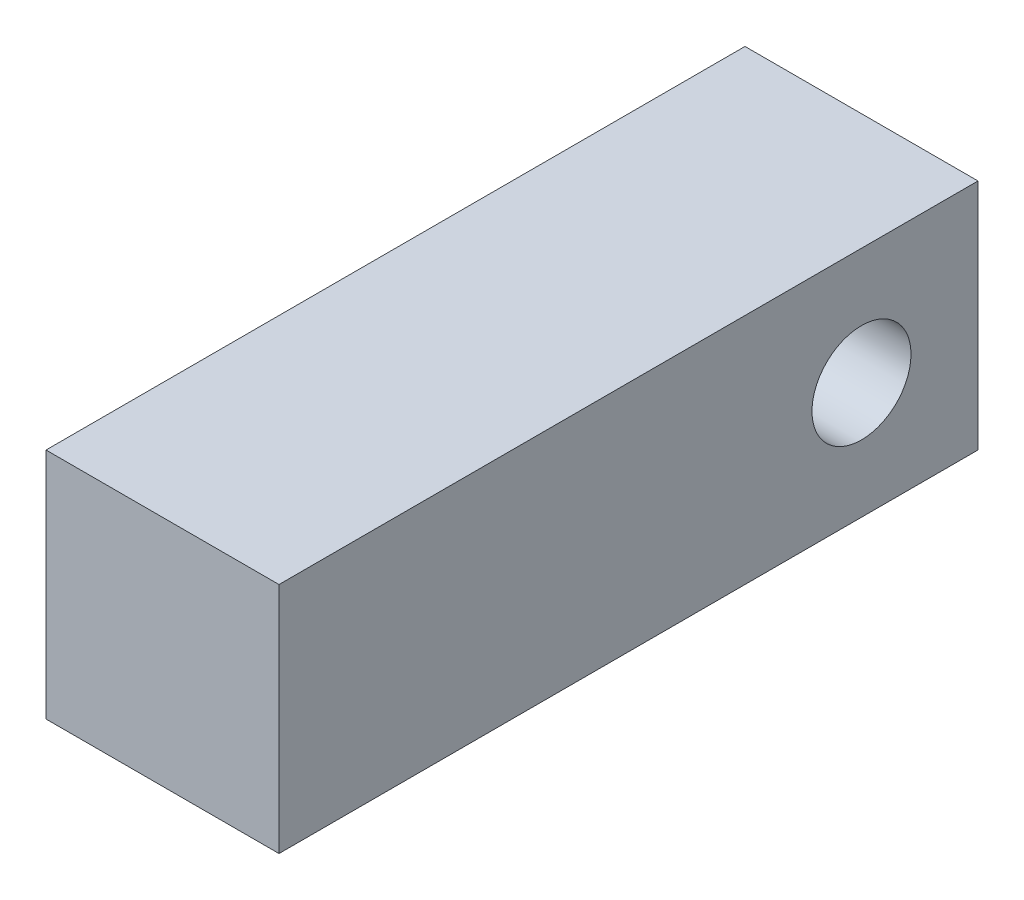
SolidWorks part; units mm, degrees
material "Pine"
ref_plane "Front Plane" through (0, 0, 0) normal (0, 0, 1) x (1, 0, 0)
ref_plane "Top Plane" through (0, 0, 0) normal (0, 1, 0) x (1, 0, 0)
ref_plane "Right Plane" through (0, 0, 0) normal (1, 0, 0) x (0, 0, -1)
sketch "Sketch1" plane through (0, 0, 0) normal (1, 0, 0) x (0, 0, -1)
  line L1 (0, 0) -> (152.4, 0)
  line L2 (0, 0) -> (0, 50.8)
  line L3 (0, 50.8) -> (152.4, 50.8)
  line L4 (152.4, 0) -> (152.4, 50.8)
  dimension "D1" = 50.8
  dimension "D2" = 152.4
extrude "Boss-Extrude1" add sketch "Sketch1" along normal blind 50.8
sketch "Sketch2" plane through (50.8, 0, 0) normal (1, 0, 0) x (0, 0, -1)
  line L0 (152.4, 0) -> (152.4, 50.8) construction
  line L1 (152.4, 50.8) -> (0, 50.8) construction
  circle A0 centre (127, 25.4) radius 10.795
  dimension "D1" = 21.59
  dimension "D2" = 25.4
  dimension "D3" = 25.4
extrude "Cut-Extrude1" cut sketch "Sketch2" against normal through all
